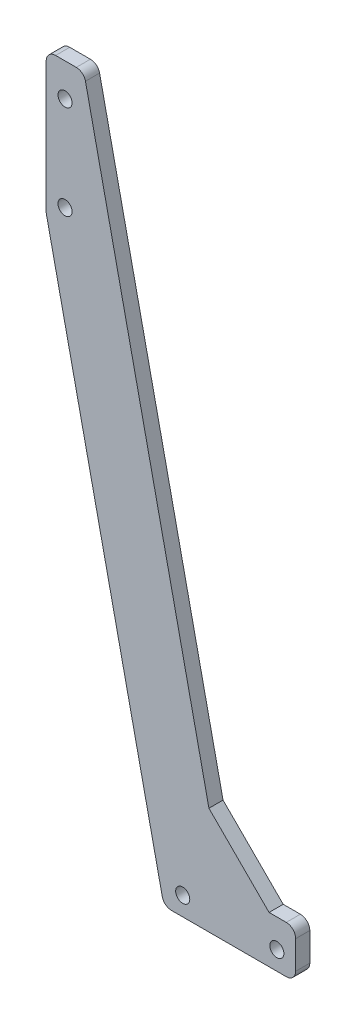
SolidWorks part; units mm, degrees
material "Thornel Mat VMA"
ref_plane "前视基准面" through (0, 0, 0) normal (0, 0, 1) x (1, 0, 0)
ref_plane "上视基准面" through (0, 0, 0) normal (0, 1, 0) x (1, 0, 0)
ref_plane "右视基准面" through (0, 0, 0) normal (1, 0, 0) x (0, 0, -1)
other "Configuration Table"
sketch "草图1" plane through (0, 0, 0) normal (0, 0, 1) x (1, 0, 0)
  line L0 (0, 0) -> (0, 198.9841) construction
  line L1 (0, 0) -> (350.1483, 0) construction
  line L2 (0, 145) -> (0, 115)
  line L3 (0, 115) -> (25, 0)
  line L4 (25, 0) -> (53, 0)
  line L7 (8, 145) -> (0, 145)
  line L8 (8, 145) -> (37.3478, 10)
  line L9 (37.3478, 10) -> (53, 10)
  line L10 (53, 10) -> (53, 0)
  circle A0 centre (4, 118) radius 1.5
  circle A1 centre (4, 138) radius 1.5
  circle A2 centre (49, 4) radius 1.5
  circle A3 centre (29, 4) radius 1.5
  dimension "D6" = 3
  dimension "D7" = 3
  dimension "D8" = 20
  dimension "D13" = 3
  dimension "D14" = 3
  dimension "D15" = 20
  dimension "D16" = 4
  dimension "D17" = 4
  dimension "D1" = 115
  dimension "D2" = 30
  dimension "D3" = 25
  dimension "D4" = 28
  dimension "D5" = 8
  dimension "D9" = 118
  dimension "D10" = 4
  dimension "D11" = 4
  dimension "D12" = 10
  dimension "D18" = 49
extrude "凸台-拉伸1" add sketch "草图1" along normal blind 3
chamfer "倒角1" distance 10 angle 45 1 edges at (37.3478, 10, 1.5)
fillet "圆角1" radius 2 6 edges at (0, 115, 1.5) (25, 0, 1.5) (53, 0, 1.5) (53, 10, 1.5) (8, 145, 1.5) (0, 145, 1.5)
